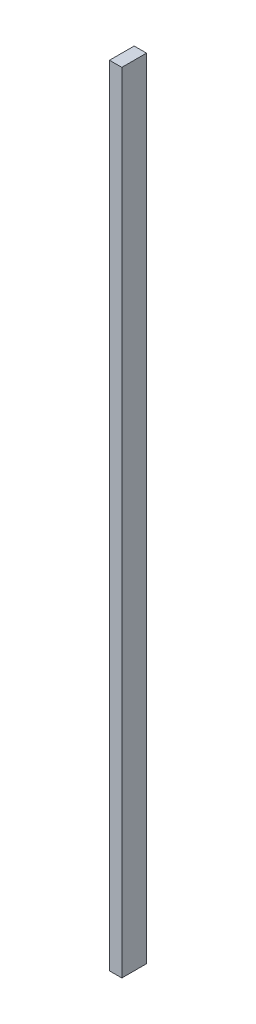
SolidWorks part; units mm, degrees
ref_plane "Спереди" through (0, 0, 0) normal (0, 0, 1) x (1, 0, 0)
ref_plane "Сверху" through (0, 0, 0) normal (0, 1, 0) x (1, 0, 0)
ref_plane "Справа" through (0, 0, 0) normal (1, 0, 0) x (0, 0, -1)
other "Configuration Table"
sketch "Эскиз1" plane through (0, 0, 0) normal (0, 1, 0) x (1, 0, 0)
  line L1 (12.5, 25) -> (-12.5, 25)
  line L2 (12.5, 25) -> (12.5, -25)
  line L3 (12.5, -25) -> (-12.5, -25)
  line L4 (-12.5, 25) -> (-12.5, -25)
  line L5 (12.5, 25) -> (-12.5, -25) construction
  line L6 (12.5, -25) -> (-12.5, 25) construction
  point P0 (0, 0)
extrude "Бобышка-Вытянуть1" add sketch "Эскиз1" along normal blind 1600
